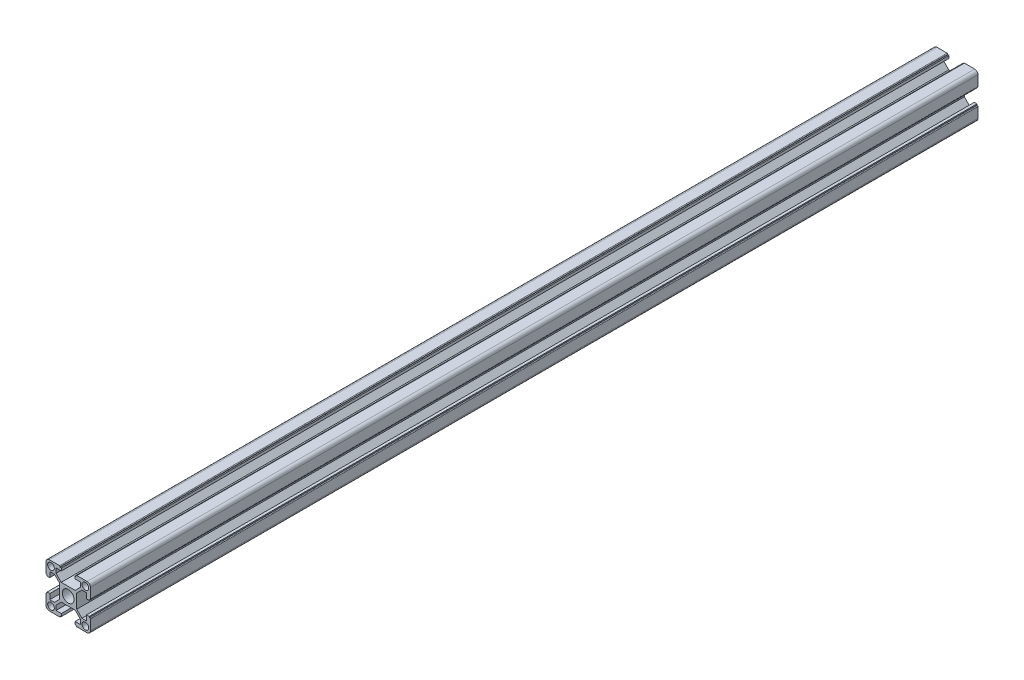
SolidWorks part; units mm, degrees
ref_plane "前视基准面" through (0, 0, 0) normal (0, 0, 1) x (1, 0, 0)
ref_plane "上视基准面" through (0, 0, 0) normal (0, 1, 0) x (1, 0, 0)
ref_plane "右视基准面" through (0, 0, 0) normal (1, 0, 0) x (0, 0, -1)
sketch "草图1" plane through (0, 0, 0) normal (0, 0, 1) x (1, 0, 0)
  line L0 (-7.75, 0) -> (0, 0) construction
  line L1 (7.75, -7.75) -> (-7.75, -7.75) construction
  line L2 (7.75, -7.75) -> (7.75, 7.75) construction
  line L3 (7.75, 7.75) -> (-7.75, 7.75) construction
  line L4 (-7.75, -7.75) -> (-7.75, 7.75) construction
  line L5 (7.75, -7.75) -> (-7.75, 7.75) construction
  line L6 (7.75, 7.75) -> (-7.75, -7.75) construction
  line L7 (0, 0) -> (0, 7.75) construction
  line L8 (3.1429, 3.85) -> (-3.1429, 3.85)
  line L9 (-3.1429, 3.85) -> (-5.5, 6.2071)
  line L10 (-5.5, 6.2071) -> (-5.5, 8.3)
  line L11 (-5.5, 8.3) -> (-3.1, 8.3)
  line L12 (-3.1, 8.3) -> (-3.1, 9.5)
  line L13 (-3.1, 9.5) -> (-3.6, 9.5)
  line L14 (-3.6, 9.5) -> (-3.6, 9.7)
  line L15 (-3.9, 10) -> (-8.5, 10)
  line L16 (-3.85, -3.1429) -> (-3.85, 3.1429)
  line L17 (-3.85, 3.1429) -> (-6.2071, 5.5)
  line L18 (-6.2071, 5.5) -> (-8.3, 5.5)
  line L19 (-8.3, 5.5) -> (-8.3, 3.1)
  line L20 (-9.5, 3.1) -> (-9.5, 3.6)
  line L21 (-8.3, 3.1) -> (-9.5, 3.1)
  line L22 (-9.5, 3.6) -> (-9.7, 3.6)
  line L23 (-10, 3.9) -> (-10, 8.5)
  line L24 (5.5, 8.3) -> (3.1, 8.3)
  line L25 (3.6, 9.5) -> (3.6, 9.7)
  line L26 (3.1, 9.5) -> (3.6, 9.5)
  line L27 (3.1, 8.3) -> (3.1, 9.5)
  line L28 (5.5, 6.2071) -> (5.5, 8.3)
  line L29 (3.1429, 3.85) -> (5.5, 6.2071)
  line L30 (3.85, -3.1429) -> (3.85, 3.1429)
  line L31 (3.85, 3.1429) -> (6.2071, 5.5)
  line L32 (9.5, 3.6) -> (9.7, 3.6)
  line L33 (8.3, 3.1) -> (9.5, 3.1)
  line L34 (9.5, 3.1) -> (9.5, 3.6)
  line L35 (8.3, 5.5) -> (8.3, 3.1)
  line L36 (6.2071, 5.5) -> (8.3, 5.5)
  line L37 (10, 3.9) -> (10, 8.5)
  line L38 (3.9, 10) -> (8.5, 10)
  line L39 (-9.5, -3.6) -> (-9.7, -3.6)
  line L40 (-8.3, -3.1) -> (-9.5, -3.1)
  line L41 (-9.5, -3.1) -> (-9.5, -3.6)
  line L42 (-8.3, -5.5) -> (-8.3, -3.1)
  line L43 (-6.2071, -5.5) -> (-8.3, -5.5)
  line L44 (-3.85, -3.1429) -> (-6.2071, -5.5)
  line L45 (-3.1429, -3.85) -> (-5.5, -6.2071)
  line L46 (-5.5, -6.2071) -> (-5.5, -8.3)
  line L47 (-3.6, -9.5) -> (-3.6, -9.7)
  line L48 (-3.1, -9.5) -> (-3.6, -9.5)
  line L49 (-3.1, -8.3) -> (-3.1, -9.5)
  line L50 (-5.5, -8.3) -> (-3.1, -8.3)
  line L51 (5.5, -6.2071) -> (5.5, -8.3)
  line L52 (3.1, -8.3) -> (3.1, -9.5)
  line L53 (3.1, -9.5) -> (3.6, -9.5)
  line L54 (3.6, -9.5) -> (3.6, -9.7)
  line L55 (5.5, -8.3) -> (3.1, -8.3)
  line L56 (3.1429, -3.85) -> (5.5, -6.2071)
  line L57 (3.1429, -3.85) -> (-3.1429, -3.85)
  line L58 (3.85, -3.1429) -> (6.2071, -5.5)
  line L59 (6.2071, -5.5) -> (8.3, -5.5)
  line L60 (8.3, -5.5) -> (8.3, -3.1)
  line L61 (9.5, -3.1) -> (9.5, -3.6)
  line L62 (8.3, -3.1) -> (9.5, -3.1)
  line L63 (9.5, -3.6) -> (9.7, -3.6)
  line L64 (3.9, -10) -> (8.5, -10)
  line L65 (10, -3.9) -> (10, -8.5)
  line L66 (-10, -3.9) -> (-10, -8.5)
  line L67 (-3.9, -10) -> (-8.5, -10)
  circle A0 centre (0, 0) radius 2.65
  circle A1 centre (-7.75, 7.75) radius 1.5
  circle A2 centre (7.75, 7.75) radius 1.5
  circle A3 centre (7.75, -7.75) radius 1.5
  circle A4 centre (-7.75, -7.75) radius 1.5
  arc A5 (-10, -8.5) -> (-8.5, -10) centre (-8.5, -8.5) ccw
  arc A6 (8.5, -10) -> (10, -8.5) centre (8.5, -8.5) ccw
  arc A7 (10, 8.5) -> (8.5, 10) centre (8.5, 8.5) ccw
  arc A8 (-8.5, 10) -> (-10, 8.5) centre (-8.5, 8.5) ccw
  arc A9 (3.6, -9.7) -> (3.9, -10) centre (3.9, -9.7) ccw
  arc A10 (-3.6, -9.7) -> (-3.9, -10) centre (-3.9, -9.7) cw
  arc A11 (-9.7, -3.6) -> (-10, -3.9) centre (-9.7, -3.9) ccw
  arc A12 (9.7, -3.6) -> (10, -3.9) centre (9.7, -3.9) cw
  arc A13 (9.7, 3.6) -> (10, 3.9) centre (9.7, 3.9) ccw
  arc A14 (-9.7, 3.6) -> (-10, 3.9) centre (-9.7, 3.9) cw
  arc A15 (3.6, 9.7) -> (3.9, 10) centre (3.9, 9.7) cw
  arc A16 (-3.6, 9.7) -> (-3.9, 10) centre (-3.9, 9.7) ccw
  point P46 (0, 3.85)
  point P56 (-3.85, 0)
  point P78 (3.85, 0)
  point P87 (-10, -10)
  point P90 (10, -10)
  point P93 (10, 10)
  point P96 (-10, 10)
  point P99 (3.6, -10)
  point P102 (-3.6, -10)
  point P105 (-10, -3.6)
  point P108 (10, -3.6)
  point P111 (10, 3.6)
  point P114 (-10, 3.6)
  point P117 (3.6, 10)
  point P120 (-3.6, 10)
  dimension "D1" = 5.3
  dimension "D2" = 3
  dimension "D11" = 1.5
  dimension "D12" = 2.25
  dimension "D13" = 0.3
  dimension "D3" = 7.7
  dimension "D4" = 6.2
  dimension "D5" = 1.7
  dimension "D6" = 1.2
  dimension "D7" = 20
  dimension "D8" = 7.2
  dimension "D9" = 11
  dimension "D10" = 1
extrude "凸台-拉伸1" add sketch "草图1" along normal mid plane 400
sketch "草图2" plane through (0, 0, 0) normal (0, 1, 0) x (1, 0, 0)
  line L0 (3.1429, 200) -> (-3.1429, 200) construction
  circle A0 centre (0, 138) radius 2.1
  circle A1 centre (0, -43) radius 2.1
  dimension "D1" = 4.2
  dimension "D2" = 62
  dimension "D3" = 181
extrude "切除-拉伸1" cut sketch "草图2" against normal through all both and the other way through all
sketch "草图3" plane through (0, -3.85, 0) normal (0, -1, 0) x (1, 0, 0)
  circle A0 centre (0, -138) radius 4.25
  circle A1 centre (0, 43) radius 4.25
  dimension "D1" = 8.5
extrude "切除-拉伸2" cut sketch "草图3" along normal through all
sketch "草图4" plane through (-3.85, 0, 0) normal (-1, 0, 0) x (0, 0, 1)
  line L1 (200, 3.1429) -> (200, -3.1429) construction
  line L2 (200, -10) -> (-200, -10) construction
  circle A0 centre (190, 0) radius 2.1
  dimension "D1" = 10
  dimension "D2" = 4.2
  dimension "D3" = 10
extrude "切除-拉伸3" cut sketch "草图4" against normal through all
